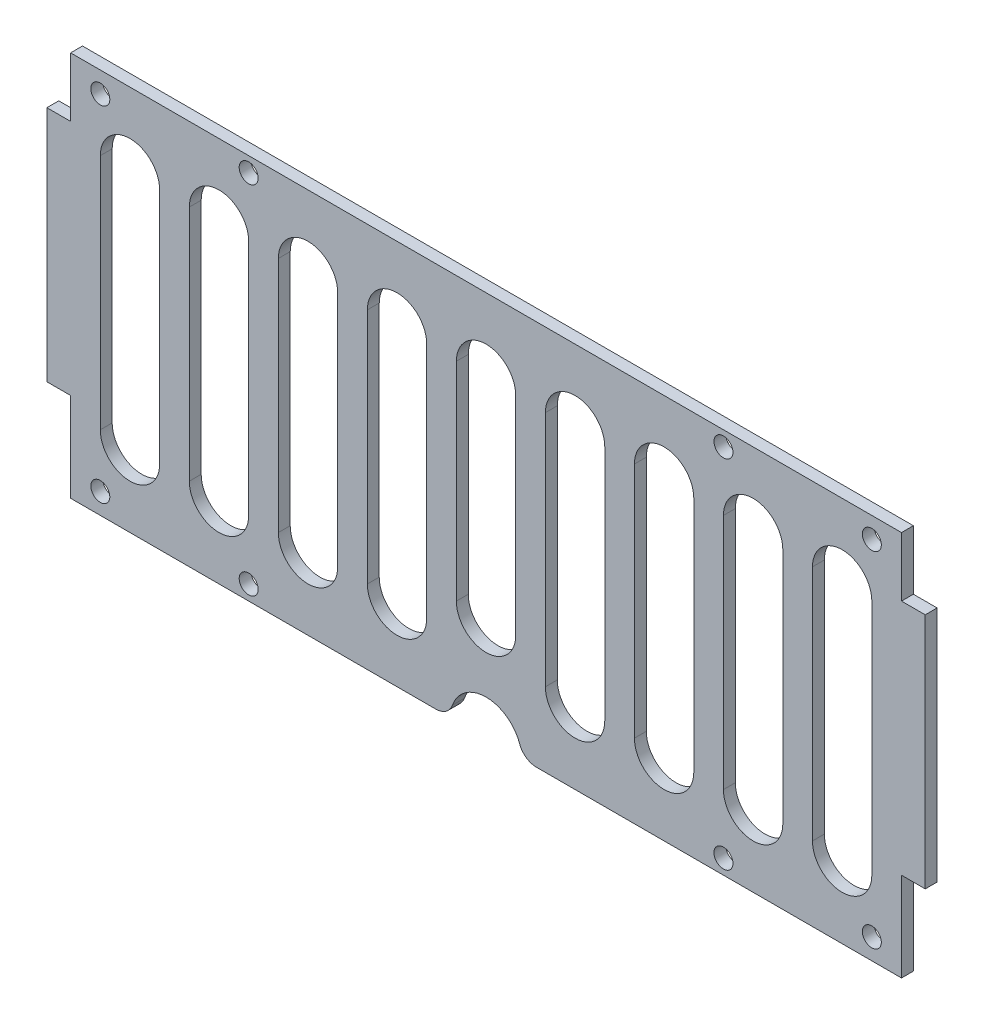
SolidWorks part; units mm, degrees
material "A-玻璃纤维"
ref_plane "前视基准面" through (0, 0, 0) normal (0, 0, 1) x (1, 0, 0)
ref_plane "上视基准面" through (0, 0, 0) normal (0, 1, 0) x (1, 0, 0)
ref_plane "右视基准面" through (0, 0, 0) normal (1, 0, 0) x (0, 0, -1)
sketch "草图1" plane through (0, 0, 0) normal (0, 0, 1) x (1, 0, 0)
  line L1 (-70, 32.5) -> (70, 32.5)
  line L2 (-70, 32.5) -> (-70, -32.5)
  line L3 (-70, -32.5) -> (70, -32.5)
  line L4 (70, 32.5) -> (70, -32.5)
  line L5 (0, -32.5) -> (0, 32.5) construction
  line L6 (-70, 0) -> (70, 0) construction
  point P0 (0, 0)
  dimension "D1" = 65
  dimension "D2" = 140
extrude "凸台-拉伸1" add sketch "草图1" along normal blind 2
sketch "草图2" plane through (0, 0, 2) normal (0, 0, 1) x (1, 0, 0)
  line L0 (0, 53.6308) -> (0, -53.8665) construction
  line L1 (-70, 32.5) -> (-70, -32.5) construction
  line L2 (-74, -17.5) -> (-70, -17.5)
  line L3 (-74, -17.5) -> (-74, 22.5)
  line L4 (-74, 22.5) -> (-70, 22.5)
  line L5 (-70, -17.5) -> (-70, 22.5)
  line L6 (-72, 22.5) -> (-72, -17.5) construction
  line L7 (-74, 2.5) -> (-70, 2.5) construction
  line L8 (70, 32.5) -> (-70, 32.5) construction
  line L9 (74, 2.5) -> (70, 2.5) construction
  line L10 (72, 22.5) -> (72, -17.5) construction
  line L11 (70, -17.5) -> (70, 22.5)
  line L12 (74, 22.5) -> (70, 22.5)
  line L13 (74, -17.5) -> (74, 22.5)
  line L14 (74, -17.5) -> (70, -17.5)
  point P3 (-72, 2.5)
  point P22 (72, 2.5)
  dimension "D1" = 40
  dimension "D2" = 4
  dimension "D3" = 10
extrude "凸台-拉伸2" add sketch "草图2" against normal blind 2
sketch "草图3" plane through (0, 0, 2) normal (0, 0, 1) x (1, 0, 0)
  line L0 (-60, -20) -> (-60, 20) construction
  line L1 (-65, -20) -> (-65, 20)
  line L2 (-55, -20) -> (-55, 20)
  line L4 (-45, -20) -> (-45, 20) construction
  line L5 (-50, -20) -> (-50, 20)
  line L6 (-40, -20) -> (-40, 20)
  line L7 (-30, -20) -> (-30, 20) construction
  line L8 (-35, -20) -> (-35, 20)
  line L9 (-25, -20) -> (-25, 20)
  line L10 (-15, -20) -> (-15, 20) construction
  line L11 (-20, -20) -> (-20, 20)
  line L12 (-10, -20) -> (-10, 20)
  line L13 (0, -20) -> (0, 20) construction
  line L14 (-5, -20) -> (-5, 20)
  line L15 (5, -20) -> (5, 20)
  line L16 (15, -20) -> (15, 20) construction
  line L17 (10, -20) -> (10, 20)
  line L18 (20, -20) -> (20, 20)
  line L19 (30, -20) -> (30, 20) construction
  line L20 (25, -20) -> (25, 20)
  line L21 (35, -20) -> (35, 20)
  line L22 (45, -20) -> (45, 20) construction
  line L23 (40, -20) -> (40, 20)
  line L24 (50, -20) -> (50, 20)
  line L25 (60, -20) -> (60, 20) construction
  line L26 (55, -20) -> (55, 20)
  line L27 (65, -20) -> (65, 20)
  arc A0 (-65, -20) -> (-55, -20) centre (-60, -20) ccw
  arc A1 (-55, 20) -> (-65, 20) centre (-60, 20) ccw
  arc A2 (-50, -20) -> (-40, -20) centre (-45, -20) ccw
  arc A3 (-40, 20) -> (-50, 20) centre (-45, 20) ccw
  arc A4 (-35, -20) -> (-25, -20) centre (-30, -20) ccw
  arc A5 (-25, 20) -> (-35, 20) centre (-30, 20) ccw
  arc A6 (-20, -20) -> (-10, -20) centre (-15, -20) ccw
  arc A7 (-10, 20) -> (-20, 20) centre (-15, 20) ccw
  arc A8 (-5, -20) -> (5, -20) centre (0, -20) ccw
  arc A9 (5, 20) -> (-5, 20) centre (0, 20) ccw
  arc A10 (10, -20) -> (20, -20) centre (15, -20) ccw
  arc A11 (20, 20) -> (10, 20) centre (15, 20) ccw
  arc A12 (25, -20) -> (35, -20) centre (30, -20) ccw
  arc A13 (35, 20) -> (25, 20) centre (30, 20) ccw
  arc A14 (40, -20) -> (50, -20) centre (45, -20) ccw
  arc A15 (50, 20) -> (40, 20) centre (45, 20) ccw
  arc A16 (55, -20) -> (65, -20) centre (60, -20) ccw
  arc A17 (65, 20) -> (55, 20) centre (60, 20) ccw
  point P2 (-60, 0)
  point P11 (-45, 0)
  point P18 (-30, 0)
  point P25 (-15, 0)
  point P32 (0, 0)
  point P39 (15, 0)
  point P46 (30, 0)
  point P53 (45, 0)
  point P60 (60, 0)
  dimension "D1" = 5
  dimension "D2" = 40
  dimension "D4" = 15
  dimension "D3" = 9
extrude "切除-拉伸1" cut sketch "草图3" against normal blind 2
sketch "草图4" plane through (0, 0, 0) normal (0, 0, -1) x (-1, 0, 0)
  line L1 (-40, 30) -> (40, 30) construction
  line L2 (-40, 30) -> (-40, -30) construction
  line L3 (-40, -30) -> (40, -30) construction
  line L4 (40, 30) -> (40, -30) construction
  line L5 (0, -30) -> (0, 30) construction
  line L6 (-40, 0) -> (40, 0) construction
  circle A0 centre (-40, -30) radius 1.6
  circle A1 centre (40, -30) radius 1.6
  circle A2 centre (40, 30) radius 1.6
  circle A3 centre (-40, 30) radius 1.6
  point P0 (0, 0)
  dimension "D3" = 3.2
  dimension "D1" = 60
  dimension "D2" = 80
extrude "切除-拉伸2" cut sketch "草图4" against normal blind 2
sketch "草图5" plane through (0, 0, 0) normal (0, 0, -1) x (-1, 0, 0)
  line L1 (-65, 29) -> (65, 29) construction
  line L2 (-65, 29) -> (-65, -29) construction
  line L3 (-65, -29) -> (65, -29) construction
  line L4 (65, 29) -> (65, -29) construction
  line L5 (0, -29) -> (0, 29) construction
  line L6 (-65, 0) -> (65, 0) construction
  circle A0 centre (-65, -29) radius 1.6
  circle A1 centre (-65, 29) radius 1.6
  circle A2 centre (65, -29) radius 1.6
  circle A3 centre (65, 29) radius 1.6
  point P0 (0, 0)
  dimension "D3" = 3.2
  dimension "D1" = 58
  dimension "D2" = 130
extrude "切除-拉伸3" cut sketch "草图5" against normal blind 2
sketch "草图6" plane through (0, 0, 0) normal (0, 0, -1) x (-1, 0, 0)
  line L0 (70, -32.5) -> (-70, -32.5) construction
  line L1 (-6, -32.5) -> (6, -32.5)
  arc A0 (-6, -32.5) -> (6, -32.5) centre (0, -32.5) cw
  dimension "D1" = 6
extrude "切除-拉伸4" cut sketch "草图6" against normal through all
fillet "圆角1" radius 3 2 edges at (6, -32.5, 1) (-6, -32.5, 1)
sketch "草图7" plane through (0, 0, 0) normal (0, 0, -1) x (-1, 0, 0)
  line L0 (-5, -20) -> (-5, 20) construction
  line L1 (5, 20) -> (5, -20) construction
  line L2 (5, -15) -> (5, -20)
  line L3 (-5, -20) -> (-5, -15)
  arc A0 (-5, -15) -> (5, -15) centre (0, -15) ccw
  arc A1 (-5, -20) -> (5, -20) centre (0, -20) ccw construction
  arc A2 (-5, -20) -> (5, -20) centre (0, -20) ccw
  dimension "D1" = 5
extrude "凸台-拉伸3" add sketch "草图7" against normal through all
